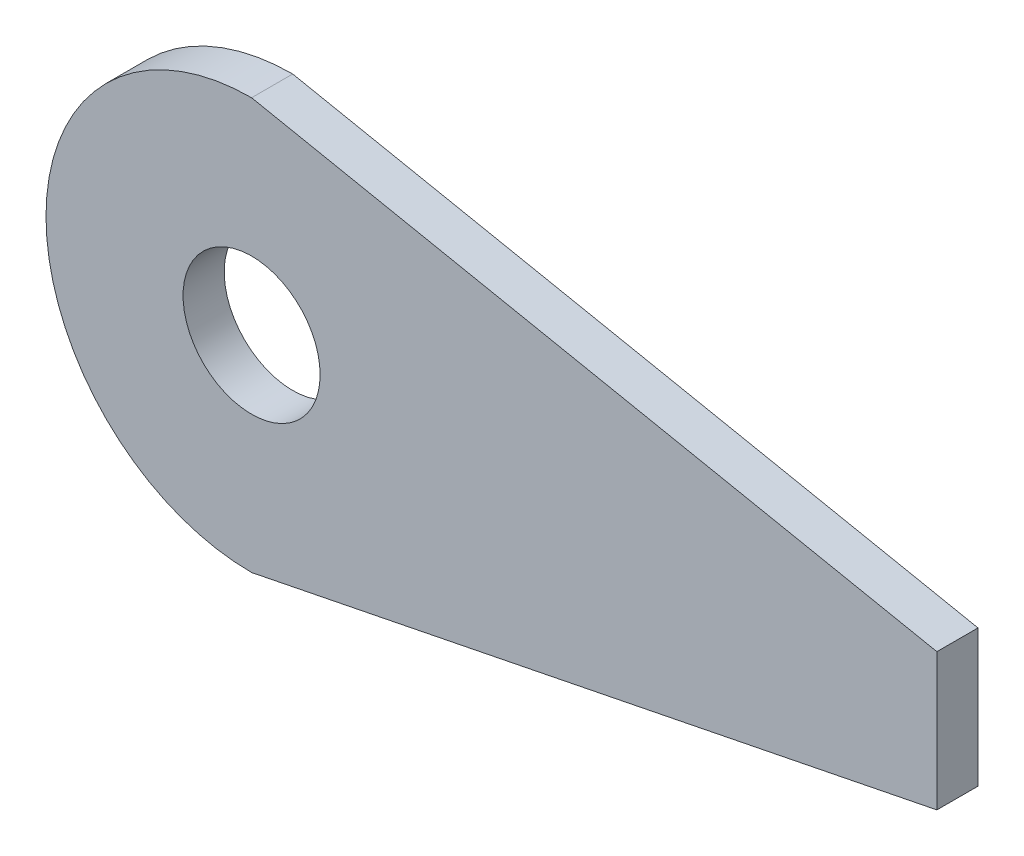
SolidWorks part; units mm, degrees
ref_plane "Front Plane" through (0, 0, 0) normal (0, 0, 1) x (1, 0, 0)
ref_plane "Top Plane" through (0, 0, 0) normal (0, 1, 0) x (1, 0, 0)
ref_plane "Right Plane" through (0, 0, 0) normal (1, 0, 0) x (0, 0, -1)
sketch "Sketch1" plane through (0, 0, 0) normal (0, 0, 1) x (1, 0, 0)
  line L0 (0, 15) -> (50, 5)
  line L1 (50, -5) -> (0, -15)
  line L2 (0, 0) -> (50, 0) construction
  line L3 (50, 5) -> (50, -5)
  circle A0 centre (0, 0) radius 5
  arc A1 (0, 15) -> (0, -15) centre (0, 0) ccw
  point P5 (50, 0)
  dimension "D1" = 10
  dimension "D2" = 10
  dimension "D3" = 10
  dimension "D4" = 50
extrude "Boss-Extrude1" add sketch "Sketch1" along normal blind 3
